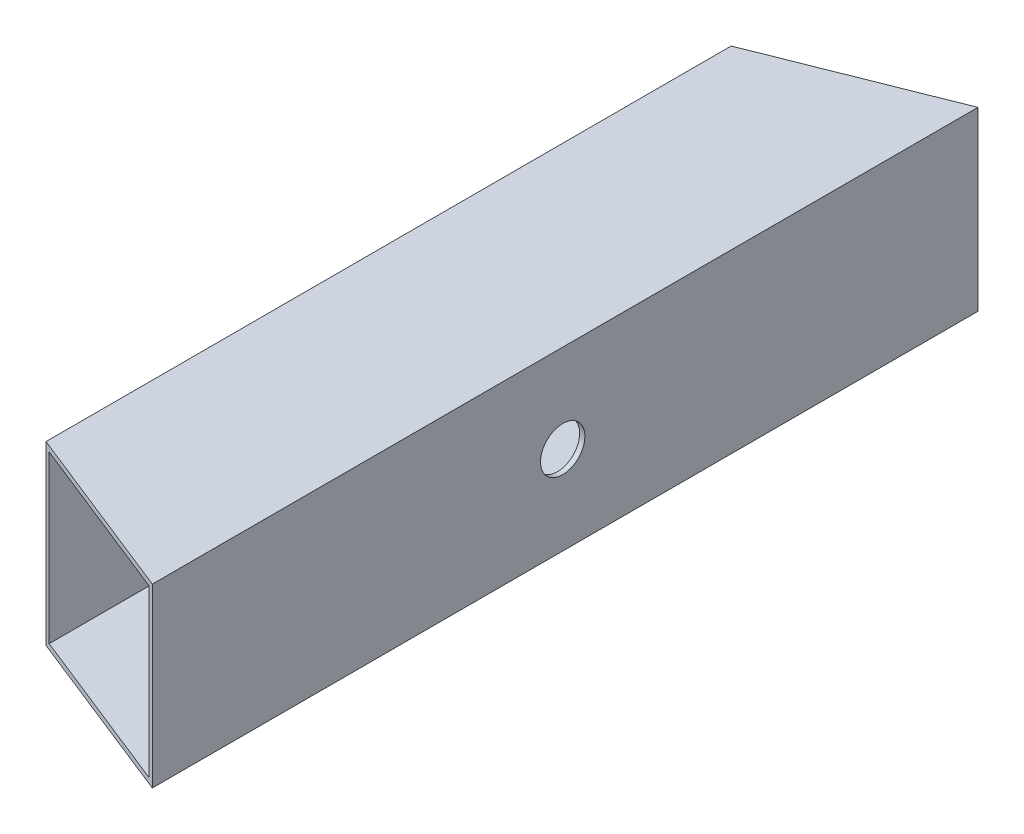
SolidWorks part; units mm, degrees
ref_plane "Plano frontal" through (0, 0, 0) normal (0, 0, 1) x (1, 0, 0)
ref_plane "Plano superior" through (0, 0, 0) normal (0, 1, 0) x (1, 0, 0)
ref_plane "Plano direito" through (0, 0, 0) normal (1, 0, 0) x (0, 0, -1)
sketch "Esboço1" plane through (0, 0, 0) normal (0, 0, 1) x (1, 0, 0)
  line L1 (-15.9452, -15.9452) -> (15.9452, -15.9452)
  line L2 (-15.9452, -15.9452) -> (-15.9452, 15.9452)
  line L3 (-15.9452, 15.9452) -> (15.9452, 15.9452)
  line L4 (15.9452, -15.9452) -> (15.9452, 15.9452)
  line L5 (-15.9452, -15.9452) -> (15.9452, 15.9452) construction
  line L6 (-15.9452, 15.9452) -> (15.9452, -15.9452) construction
  line L7 (-15, -15) -> (15, -15)
  line L8 (-15, -15) -> (-15, 15)
  line L9 (-15, 15) -> (15, 15)
  line L10 (15, -15) -> (15, 15)
  line L11 (-15, -15) -> (15, 15) construction
  line L12 (-15, 15) -> (15, -15) construction
  point P0 (0, 0)
  point P6 (0, 0)
extrude "Ressalto-extrusão1" add sketch "Esboço1" along normal blind 149.1169
ref_plane "Plano1" through (0, 0, 74.5584) normal (0, 0, -1) x (-1, 0, 0)
sketch "Esboço3" plane through (0, 15.9452, 0) normal (0, 1, 0) x (1, 0, 0)
  line L0 (15.9452, 0) -> (-15.9452, -12.6926)
  line L2 (-15.9452, -149.1169) -> (-15.9452, 0) construction
extrude "Corte-extrusão1" cut sketch "Esboço3" against normal through all and the other way through all
mirror "Espelhar5" about plane through (0, 0, 74.5584) normal (0, 0, -1) of "Corte-extrusão1"
sketch "Esboço4" plane through (-15.9452, 0, 0) normal (-1, 0, 0) x (0, 0, 1)
  circle A0 centre (75, 0) radius 4
extrude "Corte-extrusão2" cut sketch "Esboço4" against normal blind 32
